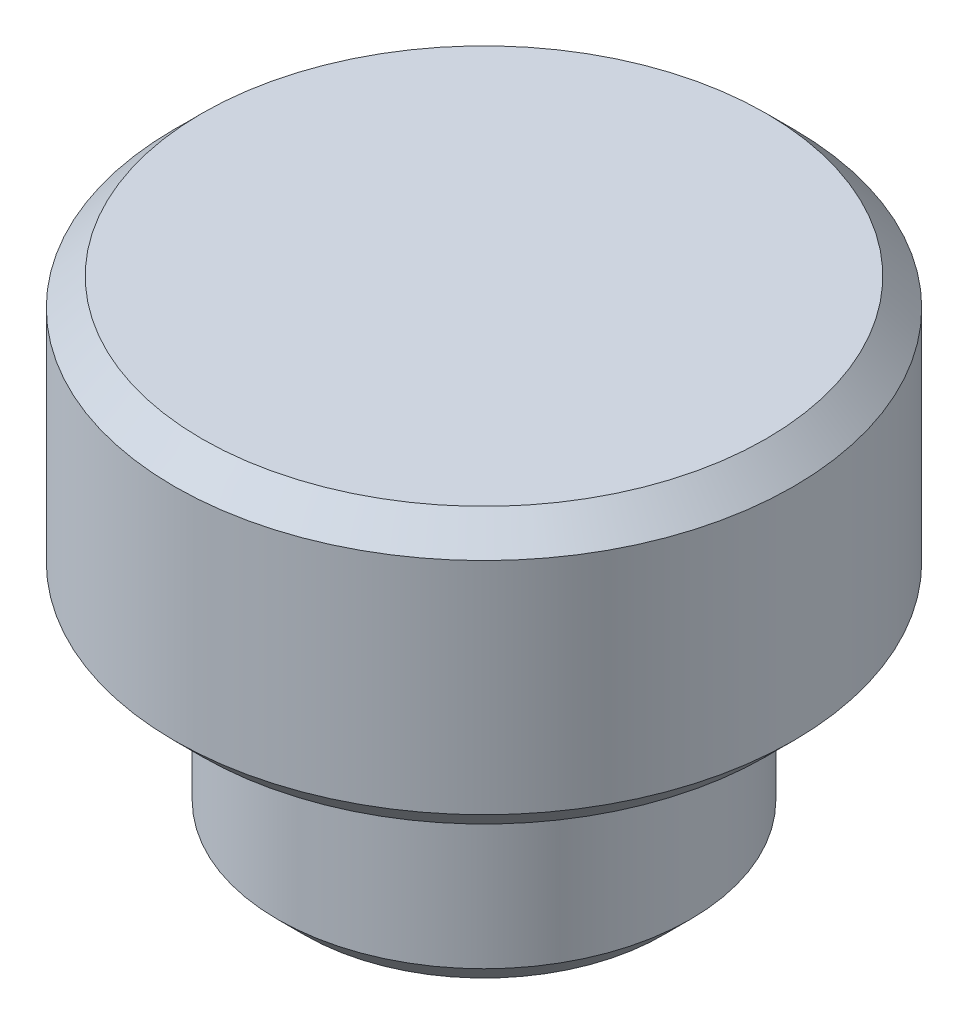
SolidWorks part; units mm, degrees
ref_plane "前视基准面" through (0, 0, 0) normal (0, 0, 1) x (1, 0, 0)
ref_plane "上视基准面" through (0, 0, 0) normal (0, 1, 0) x (1, 0, 0)
ref_plane "右视基准面" through (0, 0, 0) normal (1, 0, 0) x (0, 0, -1)
other "Configuration Table"
sketch "草图1" plane through (0, 0, 0) normal (0, 1, 0) x (1, 0, 0)
  circle A0 centre (0, 0) radius 3
  dimension "D1" = 6
extrude "凸台-拉伸1" add sketch "草图1" along normal blind 3
sketch "草图2" plane through (0, 3, 0) normal (0, 1, 0) x (1, 0, 0)
  circle A0 centre (0, 0) radius 4.5
  dimension "D1" = 9
extrude "凸台-拉伸2" add sketch "草图2" along normal blind 4
chamfer "倒角1" distance 0.4 angle 45 4 edges at (0, 3, 4.5) (0, 3, 3) (0, 0, 3) (0, 7, 4.5)
